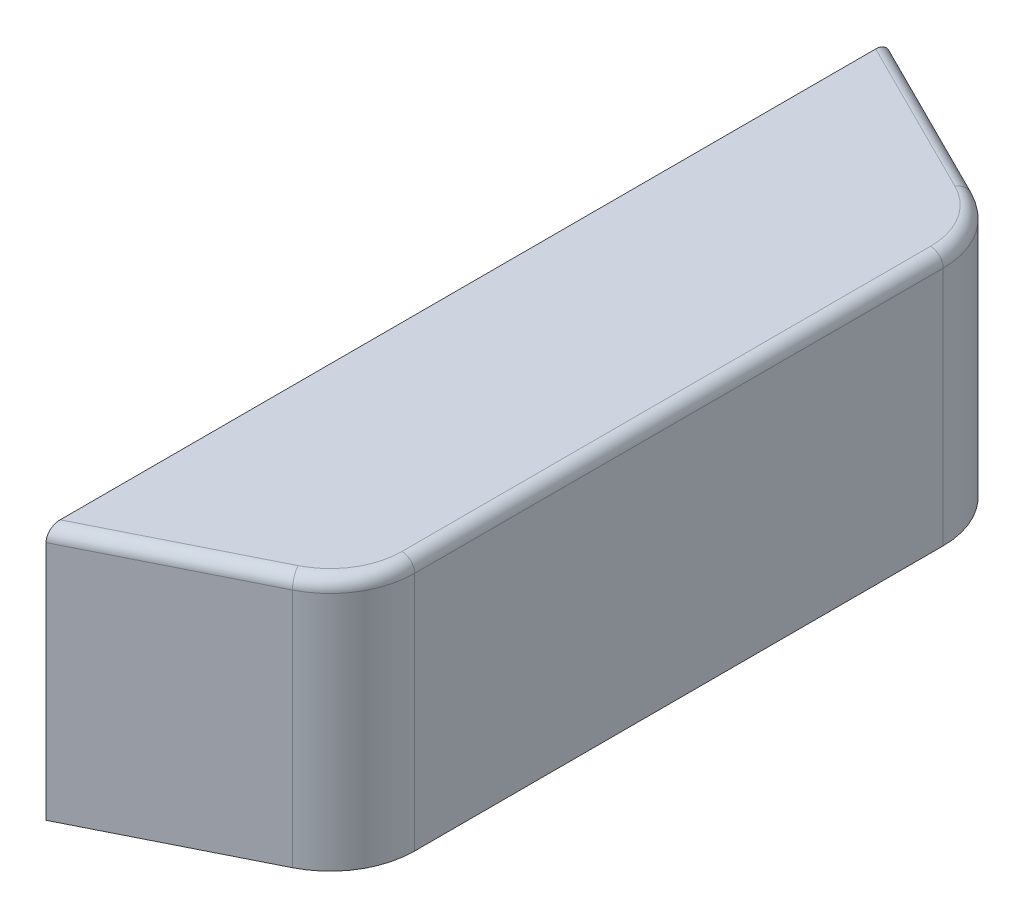
SolidWorks part; units mm, degrees
ref_plane "Front Plane" through (0, 0, 0) normal (0, 0, 1) x (1, 0, 0)
ref_plane "Top Plane" through (0, 0, 0) normal (0, 1, 0) x (1, 0, 0)
ref_plane "Right Plane" through (0, 0, 0) normal (1, 0, 0) x (0, 0, -1)
sketch "Sketch1" plane through (0, 0, 0) normal (0, 1, 0) x (1, 0, 0)
  line L0 (0, -50) -> (0, 50)
  line L1 (25, -31.3197) -> (25, 31.3197)
  line L2 (0, 50) -> (19.4721, 40.2639)
  line L3 (19.4721, -40.2639) -> (0, -50)
  line L4 (0, 0) -> (25, 0) construction
  arc A0 (19.4721, -40.2639) -> (25, -31.3197) centre (15, -31.3197) ccw
  arc A1 (19.4721, 40.2639) -> (25, 31.3197) centre (15, 31.3197) cw
  point P4 (0, 0)
  point P8 (25, 0)
  point P12 (25, -37.5)
  point P15 (25, 37.5)
  dimension "D4" = 10
  dimension "D1" = 25
  dimension "D2" = 75
  dimension "D3" = 100
extrude "Boss-Extrude1" add sketch "Sketch1" along normal blind 30
shell "Shell1" thickness 1.5
fillet "Fillet1" radius 2 8 edges at (1.5, 28.5, 0) (10.1507, 28.5, 43.2476) (22.2305, 28.5, 35.7884) (23.5, 28.5, 0) (22.2305, 28.5, -35.7884) (10.1507, 28.5, -43.2476) (1.5, 14.25, -47.5729) (1.5, 14.25, 47.5729)
fillet "Fillet2" radius 1.5 5 edges at (9.7361, 30, 45.132) (23.5065, 30, 36.577) (9.7361, 30, -45.132) (23.5065, 30, -36.577) (25, 30, 0)
